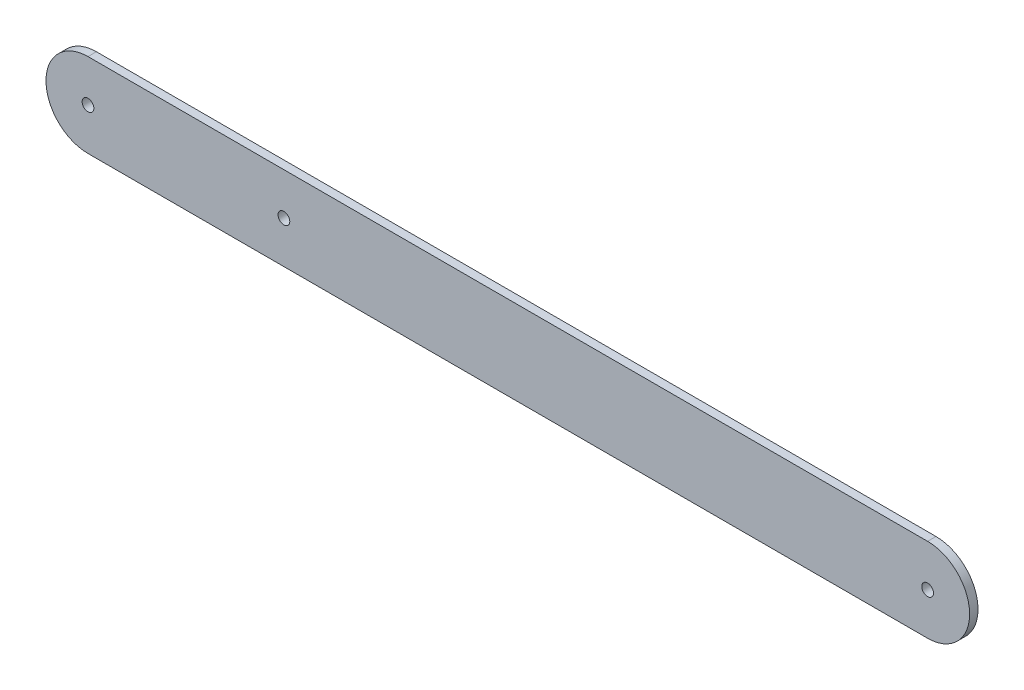
SolidWorks part; units mm, degrees
ref_plane "Plan de face" through (0, 0, 0) normal (0, 0, 1) x (1, 0, 0)
ref_plane "Plan de dessus" through (0, 0, 0) normal (0, 1, 0) x (1, 0, 0)
ref_plane "Plan de droite" through (0, 0, 0) normal (1, 0, 0) x (0, 0, -1)
sketch "Esquisse1" plane through (0, 0, 0) normal (0, 0, 1) x (1, 0, 0)
  line L0 (0, 15) -> (150, 15)
  line L1 (0, -15) -> (150, -15)
  line L2 (0, 42.9033) -> (0, -58.9726) construction
  line L3 (0, 15) -> (0, -15)
  line L4 (150, 11.2234) -> (150, -14.8682) construction
  arc A0 (150, 15) -> (150, -15) centre (150, 0) cw
  circle A1 centre (150, 0) radius 2.1
  dimension "D2" = 4.2
  dimension "D1" = 150
  dimension "D3" = 15
  dimension "D4" = 30
extrude "Boss.-Extru.1" add sketch "Esquisse1" along normal blind 3
mirror "Symétrie1" about plane through (0, 15, 3) normal (1, 0, 0) of bodies 101
sketch "Esquisse2" plane through (0, 0, 3) normal (0, 0, 1) x (1, 0, 0)
  line L1 (-32.6308, 0) -> (-58.4864, 0) construction
  circle A1 centre (-80, 0) radius 2.1
  dimension "D1" = 70
  dimension "D2" = 4.2
extrude "Enlèv. mat.-Extru.1" cut sketch "Esquisse2" against normal through all
